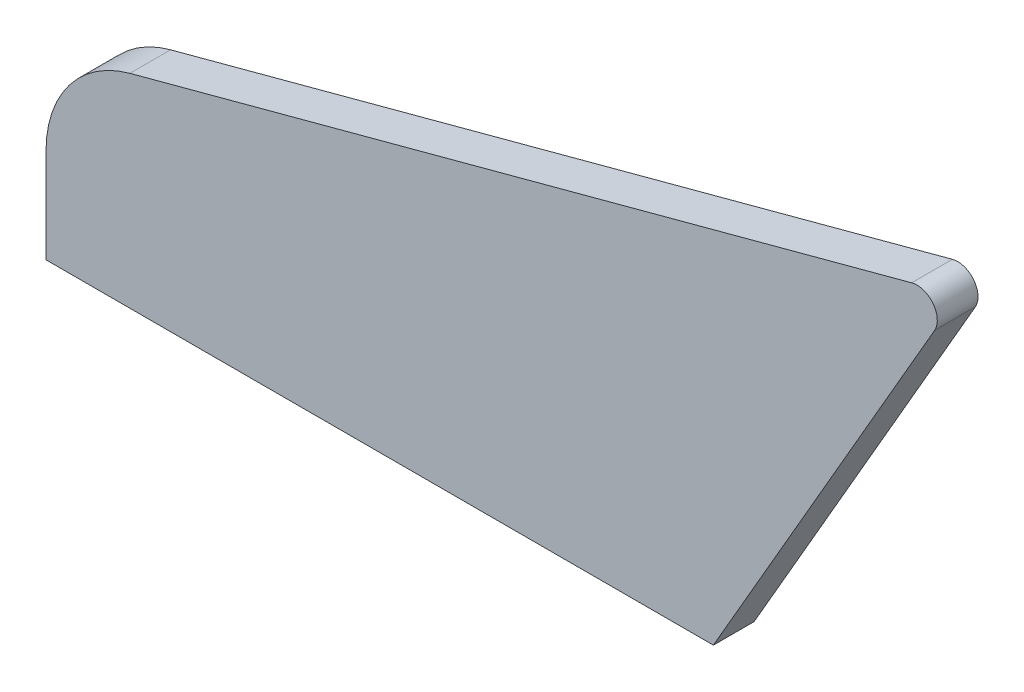
SolidWorks part; units mm, degrees
ref_plane "Plan de face" through (0, 0, 0) normal (0, 0, 1) x (1, 0, 0)
ref_plane "Plan de dessus" through (0, 0, 0) normal (0, 1, 0) x (1, 0, 0)
ref_plane "Plan de droite" through (0, 0, 0) normal (1, 0, 0) x (0, 0, -1)
sketch "Esquisse1" plane through (0, 0, 0) normal (0, 0, 1) x (1, 0, 0)
  line L0 (0, 0) -> (295, 0)
  line L1 (295, 0) -> (403.6298, 188.1523)
  line L2 (403.6298, 188.1523) -> (0, 80)
  line L3 (0, 80) -> (0, 0)
  point P2 (0, 131.8497)
  point P6 (402.123, 176.8823)
  dimension "D1" = 120
  dimension "D2" = 15
  dimension "D3" = 295
  dimension "D4" = 80
extrude "Boss.-Extru.1" add sketch "Esquisse1" along normal blind 18
fillet "Congé1" radius 50 1 edges at (0, 80, 9)
fillet "Congé2" radius 9 1 edges at (403.6298, 188.1523, 9)
